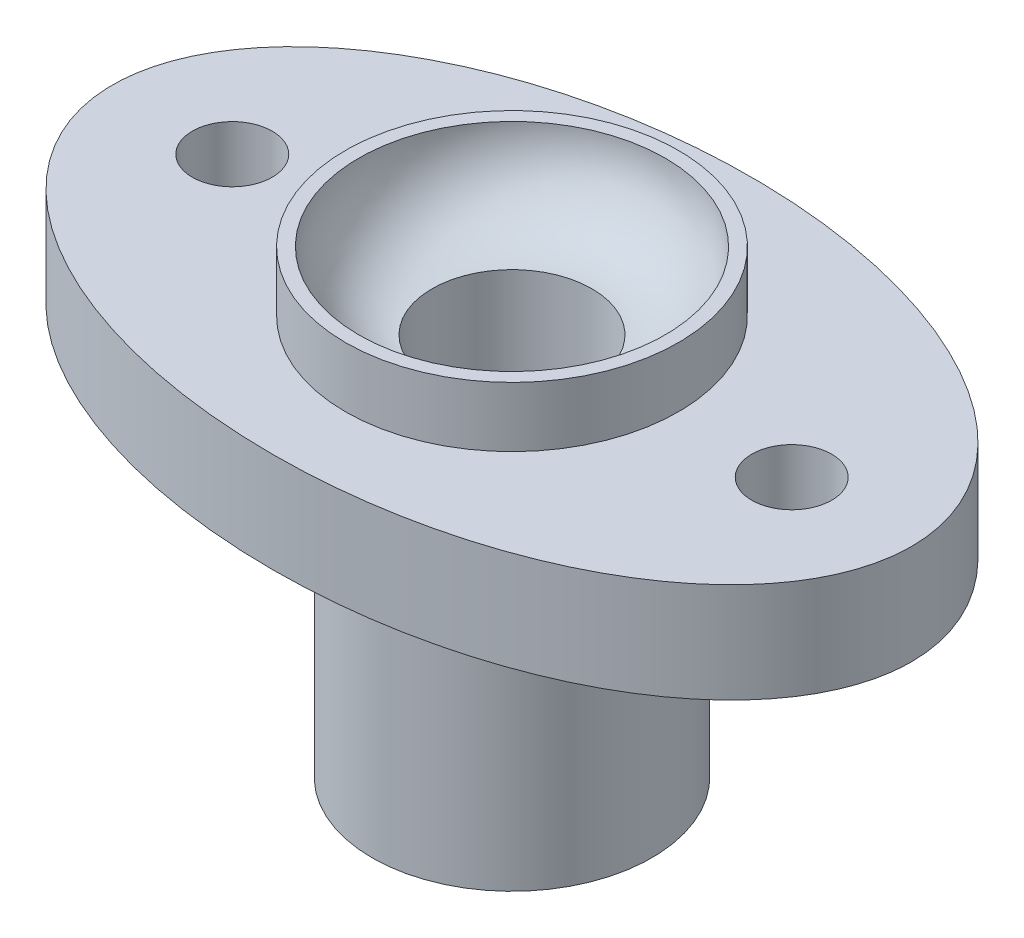
SolidWorks part; units mm, degrees
ref_plane "Front Plane" through (0, 0, 0) normal (0, 0, 1) x (1, 0, 0)
ref_plane "Top Plane" through (0, 0, 0) normal (0, 1, 0) x (1, 0, 0)
ref_plane "Right Plane" through (0, 0, 0) normal (1, 0, 0) x (0, 0, -1)
sketch "Sketch1" plane through (0, 0, 0) normal (0, 1, 0) x (1, 0, 0)
  circle A0 centre (0, 0) radius 12
  circle A1 centre (0, 0) radius 21
  dimension "D1" = 24
  dimension "D2" = 42
extrude "Boss-Extrude1" add sketch "Sketch1" along normal blind 45
sketch "Sketch4" plane through (0, 45, 0) normal (0, 1, 0) x (1, 0, 0)
  line L0 (0, 34.0165) -> (0, -34.0165) construction
  circle A0 centre (-42, 0) radius 6
  circle A1 centre (42, 0) radius 6
  circle A2 centre (0, 0) radius 12
  ellipse E0 centre (0, 0) end of major axis (60, 0) minor radius 36
  point P1 (-42, 0)
  point P13 (0, 0)
  dimension "D4" = 12
  dimension "D5" = 24
  dimension "D1" = 72
  dimension "D2" = 120
  dimension "D3" = 42
extrude "Boss-Extrude2" add sketch "Sketch4" along normal blind 15
sketch "Sketch5" plane through (0, 60, 0) normal (0, 1, 0) x (1, 0, 0)
  circle A0 centre (0, 0) radius 25
  dimension "D1" = 50
extrude "Boss-Extrude3" add sketch "Sketch5" along normal blind 9
sketch "Sketch6" plane through (0, 0, 0) normal (0, 0, 1) x (1, 0, 0)
  line L0 (0, 0) -> (0, 108.3244) construction
  line L4 (-11.5, 57.5) -> (0, 57.5)
  line L5 (-11.5, 80.5) -> (0, 80.5)
  line L6 (0, 80.5) -> (0, 57.5)
  arc A0 (-11.5, 80.5) -> (-11.5, 57.5) centre (-11.5, 69) ccw
  point P5 (-23, 69)
  point P6 (-11.5, 69)
  dimension "D2" = 11.5
  dimension "D1" = 23
revolve "Cut-Revolve1" cut sketch "Sketch6" angle 360 about L0
sketch "Sketch7" plane through (0, 0, 0) normal (0, 0, 1) x (1, 0, 0)
  line L0 (0, 0) -> (0, 84.7588) construction
  line L1 (-21, 0) -> (21, 0) construction
  line L2 (-12, 0) -> (12, 0) construction
  line L3 (0, 0) -> (21, 0)
  line L4 (0, 0) -> (12, 0)
  line L6 (-21, 0) -> (0, 5.6269)
  line L7 (0, 5.6269) -> (0, 0)
  line L8 (0, 0) -> (-21, 0)
  line L9 (0, 0) -> (-21, 0)
  line L10 (0, 5.6269) -> (0, 0)
  dimension "D1" = 15
revolve "Cut-Revolve2" cut sketch "Sketch7" angle 360 about L0
